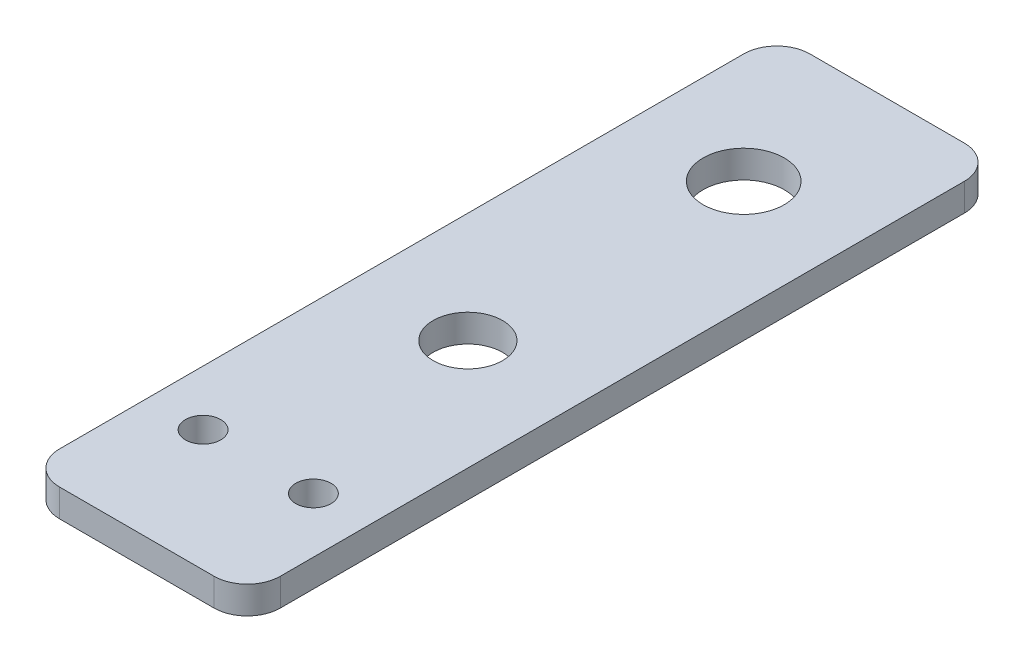
SolidWorks part; units mm, degrees
ref_plane "Front Plane" through (0, 0, 0) normal (0, 0, 1) x (1, 0, 0)
ref_plane "Top Plane" through (0, 0, 0) normal (0, 1, 0) x (1, 0, 0)
ref_plane "Right Plane" through (0, 0, 0) normal (1, 0, 0) x (0, 0, -1)
sketch "Sketch1" plane through (0, 0, 0) normal (0, 1, 0) x (1, 0, 0)
  line L0 (-12.7, -29.21) -> (-6.35, -29.21) construction
  line L1 (-12.7, -43.18) -> (12.7, -43.18)
  line L2 (-12.7, -43.18) -> (-12.7, 43.18)
  line L3 (-12.7, 43.18) -> (12.7, 43.18)
  line L4 (12.7, -43.18) -> (12.7, 43.18)
  line L5 (-12.7, -43.18) -> (12.7, 43.18) construction
  line L6 (-12.7, 43.18) -> (12.7, -43.18) construction
  line L7 (-6.35, -29.21) -> (-6.35, -43.18) construction
  line L8 (6.35, -43.18) -> (6.35, -29.21) construction
  line L9 (6.35, -29.21) -> (12.7, -29.21) construction
  line L10 (0, -43.18) -> (0, -5.08) construction
  line L11 (0, -5.08) -> (0, 26.67) construction
  line L13 (-3.302, 29.972) -> (3.302, 29.972)
  line L14 (-3.302, 29.972) -> (-3.302, 23.368)
  line L15 (-3.302, 23.368) -> (3.302, 23.368)
  line L16 (3.302, 29.972) -> (3.302, 23.368)
  line L17 (-3.302, 29.972) -> (3.302, 23.368) construction
  line L18 (-3.302, 23.368) -> (3.302, 29.972) construction
  circle A0 centre (-6.35, -29.21) radius 2.032
  circle A1 centre (6.35, -29.21) radius 2.032
  circle A2 centre (0, -5.08) radius 4
  circle A3 centre (0, 26.67) radius 4.6697
  point P0 (0, 0)
  dimension "D5" = 4.064
  dimension "D6" = 8
  dimension "D8" = 6.604
  dimension "D1" = 25.4
  dimension "D2" = 86.36
  dimension "D3" = 6.35
  dimension "D4" = 13.97
  dimension "D7" = 16.51
  dimension "D9" = 31.75
extrude "Boss-Extrude1" add sketch "Sketch1" along normal blind 3.175 contours L2 L3 L4 L1 | A2 | A3 | A0 | A1
fillet "Fillet1" radius 3.81 4 edges at (-12.7, 1.5875, 43.18) (12.7, 1.5875, 43.18) (12.7, 1.5875, -43.18) (-12.7, 1.5875, -43.18)
